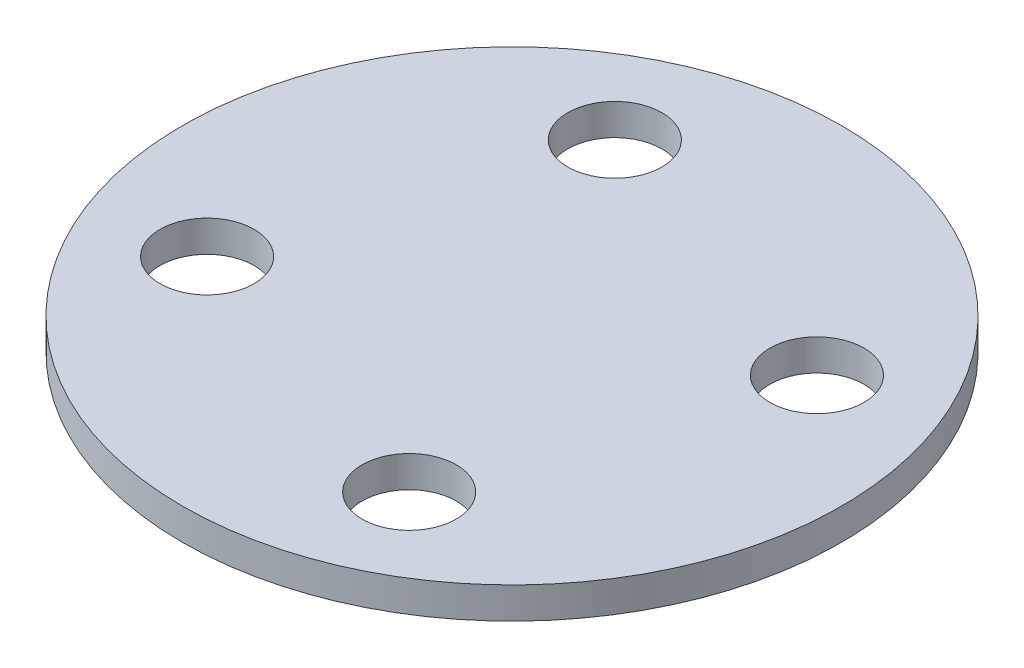
SolidWorks part; units mm, degrees
ref_plane "Front Plane" through (0, 0, 0) normal (0, 0, 1) x (1, 0, 0)
ref_plane "Top Plane" through (0, 0, 0) normal (0, 1, 0) x (1, 0, 0)
ref_plane "Right Plane" through (0, 0, 0) normal (1, 0, 0) x (0, 0, -1)
sketch "Sketch1" plane through (0, 0, 0) normal (0, 1, 0) x (1, 0, 0)
  circle A0 centre (0, 0) radius 10.5
extrude "Boss-Extrude1" add sketch "Sketch1" along normal blind 1
sketch "Sketch4" plane through (0, 0, 0) normal (0, -1, 0) x (1, 0, 0)
  circle A0 centre (6.4959, -3.2196) radius 1.5
  circle A1 centre (-3.2196, -6.4959) radius 1.5
  circle A2 centre (3.2196, 6.4959) radius 1.5
  circle A3 centre (-6.4959, 3.2196) radius 1.5
extrude "Cut-Extrude1" cut sketch "Sketch4" against normal through all
